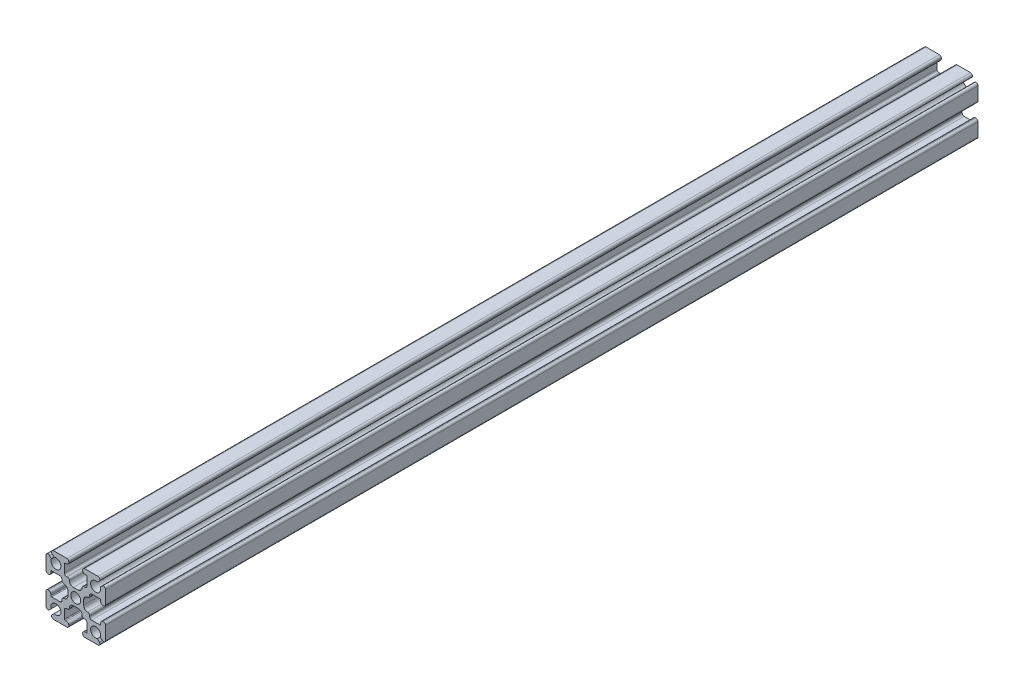
SolidWorks part; units mm, degrees
ref_plane "Front Plane" through (0, 0, 0) normal (0, 0, 1) x (1, 0, 0)
ref_plane "Top Plane" through (0, 0, 0) normal (0, 1, 0) x (1, 0, 0)
ref_plane "Right Plane" through (0, 0, 0) normal (1, 0, 0) x (0, 0, -1)
sketch "Sketch1" plane through (0, 0, 0) normal (0, 0, 1) x (1, 0, 0)
  line L0 (6.6464, 5.9393) -> (6.1636, 5.4565)
  line L1 (5.4565, 6.1636) -> (5.9393, 6.6464)
  line L2 (5.5858, 7.5) -> (2.25, 7.5)
  line L3 (1.75, 7) -> (1.75, 6.8)
  line L4 (2.25, 6.3) -> (2.65, 6.3)
  line L5 (2.85, 6.1) -> (2.85, 4)
  line L6 (2.35, 3.5) -> (2.1, 3.5)
  line L7 (0.6, 2) -> (-0.6, 2)
  line L8 (-2.1, 3.5) -> (-2.35, 3.5)
  line L9 (-2.85, 4) -> (-2.85, 6.1)
  line L10 (-2.65, 6.3) -> (-2.25, 6.3)
  line L11 (-1.75, 6.8) -> (-1.75, 7)
  line L12 (-2.25, 7.5) -> (-5.5858, 7.5)
  line L13 (-5.9393, 6.6464) -> (-5.4565, 6.1636)
  line L14 (-6.1636, 5.4565) -> (-6.6464, 5.9393)
  line L15 (-7.5, 5.5858) -> (-7.5, 2.25)
  line L16 (-7, 1.75) -> (-6.8, 1.75)
  line L17 (-6.3, 2.25) -> (-6.3, 2.65)
  line L18 (-6.1, 2.85) -> (-4, 2.85)
  line L19 (-3.5, 2.35) -> (-3.5, 2.1)
  line L20 (-2, 0.6) -> (-2, -0.6)
  line L21 (-3.5, -2.1) -> (-3.5, -2.35)
  line L22 (-4, -2.85) -> (-6.1, -2.85)
  line L23 (-6.3, -2.65) -> (-6.3, -2.25)
  line L24 (-6.8, -1.75) -> (-7, -1.75)
  line L25 (-7.5, -2.25) -> (-7.5, -5.5858)
  line L26 (-6.6464, -5.9393) -> (-6.1636, -5.4565)
  line L27 (-5.4565, -6.1636) -> (-5.9393, -6.6464)
  line L28 (-5.5858, -7.5) -> (-2.25, -7.5)
  line L29 (-1.75, -7) -> (-1.75, -6.8)
  line L30 (-2.25, -6.3) -> (-2.65, -6.3)
  line L31 (-2.85, -6.1) -> (-2.85, -4)
  line L32 (-2.35, -3.5) -> (-2.1, -3.5)
  line L33 (-0.6, -2) -> (0.6, -2)
  line L34 (2.1, -3.5) -> (2.35, -3.5)
  line L35 (2.85, -4) -> (2.85, -6.1)
  line L36 (2.65, -6.3) -> (2.25, -6.3)
  line L37 (1.75, -6.8) -> (1.75, -7)
  line L38 (2.25, -7.5) -> (5.5858, -7.5)
  line L39 (5.9393, -6.6464) -> (5.4565, -6.1636)
  line L40 (6.1636, -5.4565) -> (6.6464, -5.9393)
  line L41 (7.5, -5.5858) -> (7.5, -2.25)
  line L42 (7, -1.75) -> (6.8, -1.75)
  line L43 (6.3, -2.25) -> (6.3, -2.65)
  line L44 (6.1, -2.85) -> (4, -2.85)
  line L45 (3.5, -2.35) -> (3.5, -2.1)
  line L46 (2, -0.6) -> (2, 0.6)
  line L47 (3.5, 2.1) -> (3.5, 2.35)
  line L48 (4, 2.85) -> (6.1, 2.85)
  line L49 (6.3, 2.65) -> (6.3, 2.25)
  line L50 (6.8, 1.75) -> (7, 1.75)
  line L51 (7.5, 2.25) -> (7.5, 5.5858)
  circle A0 centre (0, 0) radius 1.25
  arc A1 (6.1636, 5.4565) -> (5.4565, 6.1636) centre (5, 5) cw
  arc A2 (5.9393, 6.6464) -> (5.5858, 7.5) centre (5.5858, 7) ccw
  arc A3 (2.25, 7.5) -> (1.75, 7) centre (2.25, 7) ccw
  arc A4 (1.75, 6.8) -> (2.25, 6.3) centre (2.25, 6.8) ccw
  arc A5 (2.65, 6.3) -> (2.85, 6.1) centre (2.65, 6.1) cw
  arc A6 (2.85, 4) -> (2.35, 3.5) centre (2.35, 4) cw
  arc A7 (2.1, 3.5) -> (1.6, 3) centre (2.1, 3) ccw
  arc A8 (1.6, 3) -> (0.6, 2) centre (0.6, 3) cw
  arc A9 (-0.6, 2) -> (-1.6, 3) centre (-0.6, 3) cw
  arc A10 (-1.6, 3) -> (-2.1, 3.5) centre (-2.1, 3) ccw
  arc A11 (-2.35, 3.5) -> (-2.85, 4) centre (-2.35, 4) cw
  arc A12 (-2.85, 6.1) -> (-2.65, 6.3) centre (-2.65, 6.1) cw
  arc A13 (-2.25, 6.3) -> (-1.75, 6.8) centre (-2.25, 6.8) ccw
  arc A14 (-1.75, 7) -> (-2.25, 7.5) centre (-2.25, 7) ccw
  arc A15 (-5.5858, 7.5) -> (-5.9393, 6.6464) centre (-5.5858, 7) ccw
  arc A16 (-5.4565, 6.1636) -> (-6.1636, 5.4565) centre (-5, 5) cw
  arc A17 (-6.6464, 5.9393) -> (-7.5, 5.5858) centre (-7, 5.5858) ccw
  arc A18 (-7.5, 2.25) -> (-7, 1.75) centre (-7, 2.25) ccw
  arc A19 (-6.8, 1.75) -> (-6.3, 2.25) centre (-6.8, 2.25) ccw
  arc A20 (-6.3, 2.65) -> (-6.1, 2.85) centre (-6.1, 2.65) cw
  arc A21 (-4, 2.85) -> (-3.5, 2.35) centre (-4, 2.35) cw
  arc A22 (-3.5, 2.1) -> (-3, 1.6) centre (-3, 2.1) ccw
  arc A23 (-3, 1.6) -> (-2, 0.6) centre (-3, 0.6) cw
  arc A24 (-2, -0.6) -> (-3, -1.6) centre (-3, -0.6) cw
  arc A25 (-3, -1.6) -> (-3.5, -2.1) centre (-3, -2.1) ccw
  arc A26 (-3.5, -2.35) -> (-4, -2.85) centre (-4, -2.35) cw
  arc A27 (-6.1, -2.85) -> (-6.3, -2.65) centre (-6.1, -2.65) cw
  arc A28 (-6.3, -2.25) -> (-6.8, -1.75) centre (-6.8, -2.25) ccw
  arc A29 (-7, -1.75) -> (-7.5, -2.25) centre (-7, -2.25) ccw
  arc A30 (-7.5, -5.5858) -> (-6.6464, -5.9393) centre (-7, -5.5858) ccw
  arc A31 (-6.1636, -5.4565) -> (-5.4565, -6.1636) centre (-5, -5) cw
  arc A32 (-5.9393, -6.6464) -> (-5.5858, -7.5) centre (-5.5858, -7) ccw
  arc A33 (-2.25, -7.5) -> (-1.75, -7) centre (-2.25, -7) ccw
  arc A34 (-1.75, -6.8) -> (-2.25, -6.3) centre (-2.25, -6.8) ccw
  arc A35 (-2.65, -6.3) -> (-2.85, -6.1) centre (-2.65, -6.1) cw
  arc A36 (-2.85, -4) -> (-2.35, -3.5) centre (-2.35, -4) cw
  arc A37 (-2.1, -3.5) -> (-1.6, -3) centre (-2.1, -3) ccw
  arc A38 (-1.6, -3) -> (-0.6, -2) centre (-0.6, -3) cw
  arc A39 (0.6, -2) -> (1.6, -3) centre (0.6, -3) cw
  arc A40 (1.6, -3) -> (2.1, -3.5) centre (2.1, -3) ccw
  arc A41 (2.35, -3.5) -> (2.85, -4) centre (2.35, -4) cw
  arc A42 (2.85, -6.1) -> (2.65, -6.3) centre (2.65, -6.1) cw
  arc A43 (2.25, -6.3) -> (1.75, -6.8) centre (2.25, -6.8) ccw
  arc A44 (1.75, -7) -> (2.25, -7.5) centre (2.25, -7) ccw
  arc A45 (5.5858, -7.5) -> (5.9393, -6.6464) centre (5.5858, -7) ccw
  arc A46 (5.4565, -6.1636) -> (6.1636, -5.4565) centre (5, -5) cw
  arc A47 (6.6464, -5.9393) -> (7.5, -5.5858) centre (7, -5.5858) ccw
  arc A48 (7.5, -2.25) -> (7, -1.75) centre (7, -2.25) ccw
  arc A49 (6.8, -1.75) -> (6.3, -2.25) centre (6.8, -2.25) ccw
  arc A50 (6.3, -2.65) -> (6.1, -2.85) centre (6.1, -2.65) cw
  arc A51 (4, -2.85) -> (3.5, -2.35) centre (4, -2.35) cw
  arc A52 (3.5, -2.1) -> (3, -1.6) centre (3, -2.1) ccw
  arc A53 (3, -1.6) -> (2, -0.6) centre (3, -0.6) cw
  arc A54 (2, 0.6) -> (3, 1.6) centre (3, 0.6) cw
  arc A55 (3, 1.6) -> (3.5, 2.1) centre (3, 2.1) ccw
  arc A56 (3.5, 2.35) -> (4, 2.85) centre (4, 2.35) cw
  arc A57 (6.1, 2.85) -> (6.3, 2.65) centre (6.1, 2.65) cw
  arc A58 (6.3, 2.25) -> (6.8, 1.75) centre (6.8, 2.25) ccw
  arc A59 (7, 1.75) -> (7.5, 2.25) centre (7, 2.25) ccw
  arc A60 (7.5, 5.5858) -> (6.6464, 5.9393) centre (7, 5.5858) ccw
extrude "Boss-Extrude1" add sketch "Sketch1" along normal blind 220
